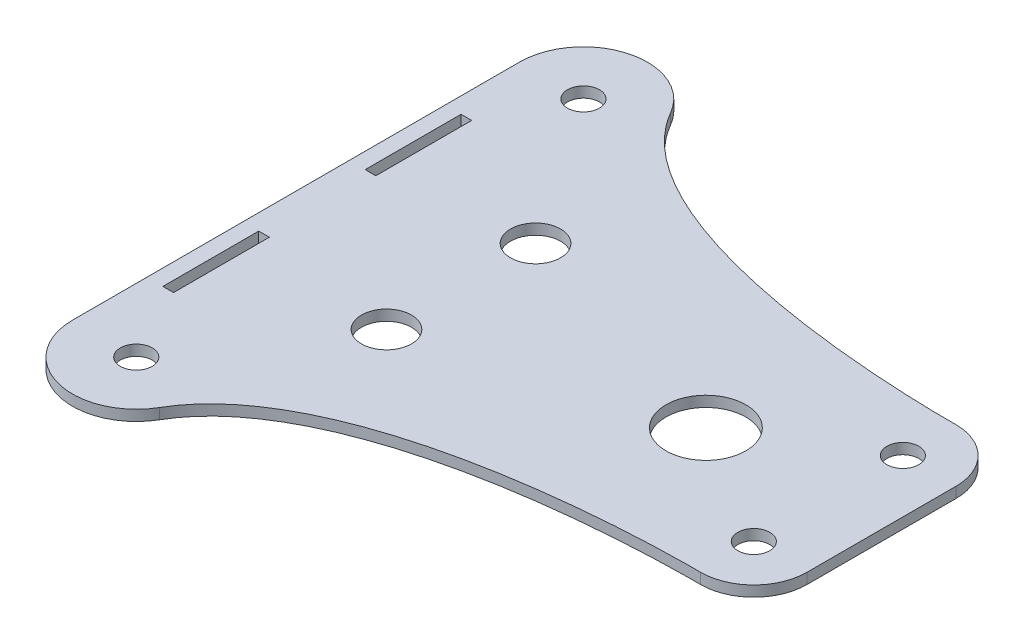
SolidWorks part; units mm, degrees
ref_plane "Plan de face" through (0, 0, 0) normal (0, 0, 1) x (1, 0, 0)
ref_plane "Plan de dessus" through (0, 0, 0) normal (0, 1, 0) x (1, 0, 0)
ref_plane "Plan de droite" through (0, 0, 0) normal (1, 0, 0) x (0, 0, -1)
sketch "Esquisse1" plane through (0, 0, 0) normal (0, 1, 0) x (1, 0, 0)
  line L0 (0, 270) -> (570, 270) construction
  line L1 (0, 0) -> (570, 0) construction
  line L2 (0, 0) -> (0, 540) construction
  line L3 (0, 540) -> (570, 540) construction
  line L4 (570, 0) -> (570, 540) construction
  line L5 (80, 480) -> (20, 480) construction
  line L6 (80, 480) -> (80, 60) construction
  line L7 (520, 340) -> (520, 200) construction
  line L8 (0, 340) -> (520, 340) construction
  line L9 (520, 200) -> (0, 200) construction
  line L10 (80, 60) -> (20, 60) construction
  line L11 (20, 480) -> (20, 60)
  line L12 (520, 340) -> (570, 340) construction
  line L13 (520, 200) -> (570, 200) construction
  line L14 (570, 340) -> (570, 200)
  line L15 (131.9615, 30) -> (80, 60) construction
  line L16 (80, 480) -> (131.9615, 510) construction
  line L17 (520, 390) -> (520, 340) construction
  line L18 (520, 200) -> (520, 150) construction
  line L19 (415, 477) -> (80, 477) construction
  line L20 (415, 477) -> (415, 540) construction
  line L21 (155, 453) -> (155, 540) construction
  line L22 (155, 453) -> (80, 453) construction
  line L23 (175, 340) -> (175, 200) construction
  circle A0 centre (405, 270) radius 37.5
  arc A1 (131.9615, 510) -> (20, 480) centre (80, 480) ccw
  arc A2 (520, 390) -> (570, 340) centre (520, 340) cw
  circle A3 centre (520, 200) radius 15
  circle A4 centre (520, 340) radius 15
  circle A5 centre (80, 480) radius 15
  circle A6 centre (80, 60) radius 15
  arc A7 (520, 150) -> (570, 200) centre (520, 200) ccw
  arc A8 (20, 60) -> (131.9615, 30) centre (80, 60) ccw
  circle A9 centre (175, 340) radius 23.5
  circle A10 centre (175, 200) radius 23.5
  spline S0 degree 3 poles (131.9615, 30) (204.7288, 156.0366) (519.6712, 149.9197) (520, 150) knots 0 0 0 0 1 1 1 1
  spline S1 degree 3 poles (131.9615, 510) (204.7288, 383.9634) (519.6712, 390.0803) (520, 390) knots 0 0 0 0 1 1 1 1
  point P10 (520, 270)
  point P22 (80, 270)
  point P37 (175, 270)
  dimension "D2" = 30
  dimension "D3" = 30
  dimension "D4" = 30
  dimension "D5" = 30
  dimension "D11" = 75
  dimension "D13" = 47
  dimension "D14" = 50
  dimension "D17" = 63
  dimension "D22" = 47
  dimension "D1" = 140
  dimension "D6" = 550
  dimension "D7" = 140
  dimension "D8" = 80
  dimension "D9" = 50
  dimension "D10" = 60
  dimension "D12" = 115
  dimension "D15" = 70
  dimension "D16" = 150
  dimension "D18" = 155
  dimension "D20" = 87
  dimension "D21" = 95
extrude "Boss.-Extru.2" add sketch "Esquisse1" along normal blind 10
sketch "Esquisse2" plane through (0, 10, 0) normal (0, 1, 0) x (1, 0, 0)
  line L0 (35, 130) -> (45, 130)
  line L1 (20, 480) -> (20, 60) construction
  line L2 (45, 130) -> (45, 220)
  line L3 (45, 220) -> (35, 220)
  line L4 (35, 320) -> (35, 410)
  line L5 (20, 270) -> (570, 270) construction
  line L6 (570, 200) -> (570, 340) construction
  line L7 (35, 220) -> (35, 130)
  line L8 (45, 320) -> (35, 320)
  line L9 (45, 410) -> (45, 320)
  line L10 (35, 410) -> (45, 410)
  dimension "D1" = 10
  dimension "D2" = 90
  dimension "D3" = 50
  dimension "D4" = 15
extrude "Enlèv. mat.-Extru.1" cut sketch "Esquisse2" against normal blind 10
